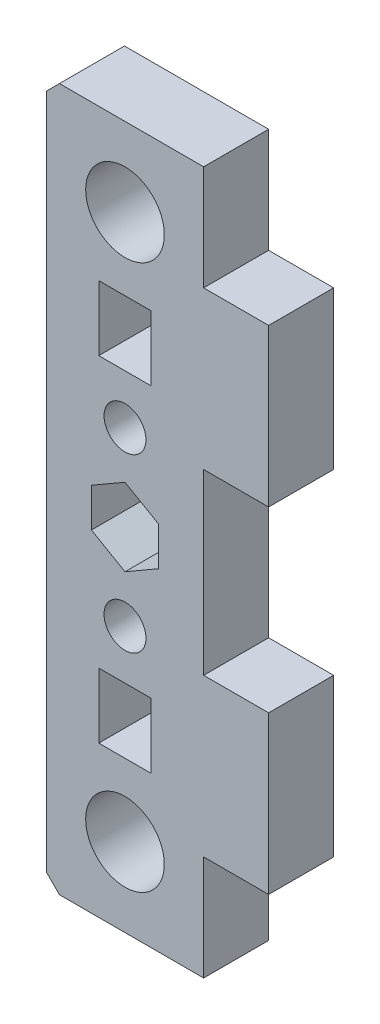
SolidWorks part; units mm, degrees
ref_plane "Front Plane" through (0, 0, 0) normal (0, 0, 1) x (1, 0, 0)
ref_plane "Top Plane" through (0, 0, 0) normal (0, 1, 0) x (1, 0, 0)
ref_plane "Right Plane" through (0, 0, 0) normal (1, 0, 0) x (0, 0, -1)
sketch "Model" plane through (0, 0, 0) normal (0, 0, 1) x (1, 0, 0)
  line L0 (-12.5, 0) -> (-15, 2.5)
  line L1 (-12.5, 134) -> (-15, 131.5)
  line L2 (15, 129) -> (-15, 129) construction
  line L26 (0, 0) -> (0, 134) construction
  line L33 (-12.5, 0) -> (15, 0)
  line L34 (-15, 2.5) -> (-15, 131.5)
  line L35 (-12.5, 134) -> (15, 134)
  line L36 (15, 0) -> (15, 20)
  line L37 (15, 50) -> (15, 84)
  line L38 (15, 20) -> (27.4, 20)
  line L39 (-15, 67) -> (15, 67) construction
  line L40 (15, 50) -> (27.4, 50)
  line L41 (27.4, 20) -> (27.4, 50)
  line L42 (15, 114) -> (27.4, 114)
  line L43 (27.4, 114) -> (27.4, 84)
  line L44 (15, 84) -> (27.4, 84)
  line L45 (15, 114) -> (15, 134)
  line L46 (-5, 92.8) -> (-5, 105.2)
  line L47 (0, 74.3901) -> (-6.4, 70.695)
  line L48 (-6.4, 70.695) -> (-6.4, 63.305)
  line L49 (-6.4, 63.305) -> (0, 59.6099)
  line L50 (0, 59.6099) -> (6.4, 63.305)
  line L51 (6.4, 63.305) -> (6.4, 70.695)
  line L52 (6.4, 70.695) -> (0, 74.3901)
  line L53 (-5, 41.2) -> (5, 41.2)
  line L54 (-5, 41.2) -> (-5, 28.8)
  line L55 (-5, 28.8) -> (5, 28.8)
  line L56 (5, 41.2) -> (5, 28.8)
  line L57 (-5, 41.2) -> (5, 28.8) construction
  line L58 (-5, 28.8) -> (5, 41.2) construction
  line L59 (-5, 92.8) -> (5, 92.8)
  line L60 (-5, 105.2) -> (5, 92.8) construction
  line L61 (-5, 92.8) -> (5, 105.2) construction
  line L62 (5, 92.8) -> (5, 105.2)
  line L63 (-5, 105.2) -> (5, 105.2)
  circle A0 centre (0, 50.6099) radius 4
  circle A1 centre (0, 83.3901) radius 4
  circle A3 centre (0, 15) radius 7.5
  circle A4 centre (0, 119) radius 7.5
  circle A5 centre (0, 67) radius 6.4 construction
  point P10 (0, 129)
  point P50 (0, 67)
  point P60 (0, 35)
  point P72 (0, 99)
  dimension "D20" = 15
  dimension "D3" = 8
  dimension "D4" = 12.4
  dimension "D6" = 30
  dimension "D7" = 30
  dimension "D9" = 134
  dimension "D10" = 20
  dimension "D17" = 12.4
  dimension "D18" = 15
  dimension "D22" = 10
  dimension "D13" = 12.8
  dimension "D5" = 5
  dimension "D8" = 20
  dimension "D11" = 2.5
  dimension "D12" = 135
  dimension "D14" = 5
extrude "Boss-Extrude1" add sketch "Model" along normal blind 12.4
equation "\"material-thickness\" = 12.4mm"
equation "\"tab-width-small\" = 20mm ' Width of the small version of the Tab"
equation "\"tab-width-large\" = 30mm ' Width of the large version of the Tab"
equation "\"linear-bar-bearingouter-dia\" = 15mm ' Diameter of the outer side of the bearing"
equation "\"linear-thread-nut-dia\" = 12.8mm ' Outer Diameter of the Nut used on the X Axis, typically M8 = 10mm"
equation "\"linear-bar-dia\" = 8mm ' Diameter of the metal slide bar used on the X Axis"
equation "\"D1@Boss-Extrude1\"=\"material-thickness\""
equation "\"D4@Model\"=\"material-thickness\""
equation "\"D6@Model\"=\"tab-width-large\""
equation "\"D17@Model\"=\"material-thickness\""
equation "\"D20@Model\"=\"linear-bar-bearingouter-dia\""
equation "\"D13@Model\"=\"linear-thread-nut-dia\""
equation "\"D3@Model\"=\"linear-bar-dia\""
